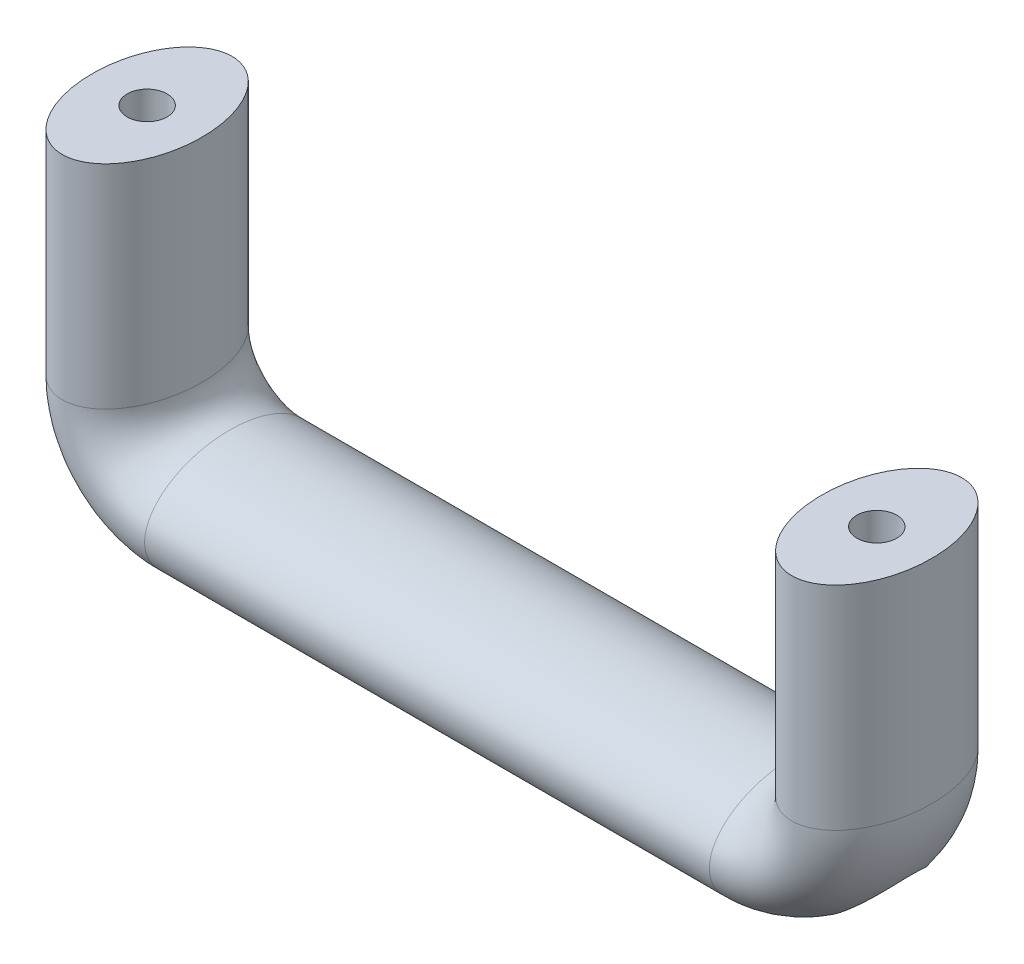
SolidWorks part; units mm, degrees
material "6061-T6 (SS)"
ref_plane "Front Plane" through (0, 0, 0) normal (0, 0, 1) x (1, 0, 0)
ref_plane "Top Plane" through (0, 0, 0) normal (0, 1, 0) x (1, 0, 0)
ref_plane "Right Plane" through (0, 0, 0) normal (1, 0, 0) x (0, 0, -1)
sketch "Sketch1" plane through (0, 0, 0) normal (0, 0, 1) x (1, 0, 0)
  line L0 (-57.9438, 46.8312) -> (-57.9438, 13.0969) construction
  line L1 (-44.8469, 0) -> (44.8469, 0) construction
  line L2 (57.9438, 13.0969) -> (57.9437, 46.8312) construction
  line L3 (-66.675, 46.8313) -> (-49.2125, 46.8313) construction
  line L4 (49.2125, 46.8312) -> (66.675, 46.8312) construction
  line L5 (-57.9438, -8.7312) -> (57.9438, -8.7312) construction
  line L7 (-61.1187, 46.8312) -> (-54.7688, 46.8312) construction
  line L8 (-61.1187, 46.8312) -> (-61.1187, 29.3687) construction
  line L9 (-61.1187, 29.3687) -> (-54.7687, 29.3687) construction
  line L10 (-54.7688, 46.8312) -> (-54.7687, 29.3687) construction
  line L11 (54.7688, 46.8312) -> (61.1187, 46.8312) construction
  line L12 (54.7688, 46.8312) -> (54.7688, 29.3687) construction
  line L13 (54.7688, 29.3687) -> (61.1187, 29.3687) construction
  line L14 (61.1187, 46.8312) -> (61.1187, 29.3687) construction
  arc A0 (-57.9438, 13.0969) -> (-44.8469, 0) centre (-44.8469, 13.0969) ccw construction
  arc A1 (44.8469, 0) -> (57.9438, 13.0969) centre (44.8469, 13.0969) ccw construction
  point P11 (-57.9438, 29.3687)
  dimension "D2" = 13.0969
  dimension "D1" = 8.7312
  dimension "A" = 115.8875
  dimension "Projected Dis" = 55.5625
  dimension "Thread Dia" = 6.35
  dimension "Thread Depth" = 17.4625
  dimension "width" = 17.4625
ref_plane "Plane1" through (0, 46.8312, 0) normal (0, 1, 0) x (-1, 0, 0)
sketch "Sketch2" plane through (0, 46.8312, 0) normal (0, 1, 0) x (-1, 0, 0)
  ellipse E0 centre (57.9438, 0) end of major axis (57.9438, -13.4937) minor radius 8.7312
  dimension "D1" = 26.9875
sketch "Sketch3" plane through (0, 0, 0) normal (0, 0, 1) x (1, 0, 0)
  line L0 (57.9438, 13.0969) -> (57.9437, 46.8312) construction
  line L1 (-44.8469, 0) -> (44.8469, 0) construction
  line L2 (-57.9438, 46.8312) -> (-57.9438, 13.0969) construction
  line L3 (57.9438, 13.0969) -> (57.9437, 46.8312)
  line L4 (-44.8469, 0) -> (44.8469, 0)
  line L5 (-57.9438, 46.8312) -> (-57.9438, 13.0969)
  arc A0 (44.8469, 0) -> (57.9438, 13.0969) centre (44.8469, 13.0969) ccw construction
  arc A1 (-57.9438, 13.0969) -> (-44.8469, 0) centre (-44.8469, 13.0969) ccw construction
  arc A2 (44.8469, 0) -> (57.9438, 13.0969) centre (44.8469, 13.0969) ccw
  arc A3 (-57.9438, 13.0969) -> (-44.8469, 0) centre (-44.8469, 13.0969) ccw
sketch "Sketch8" plane through (0, 46.8312, 0) normal (0, 1, 0) x (-1, 0, 0)
  line L0 (57.9438, -13.4937) -> (57.9438, 13.4937) construction
  dimension "height" = 26.9875
ref_plane "Plane2" through (-57.9438, 0, 0) normal (1, 0, 0) x (0, 0, -1)
sweep "Sweep1" add profiles "Sketch2" path "Sketch3"
sketch "Sketch4" plane through (0, 46.8312, 0) normal (0, 1, 0) x (-1, 0, 0)
  circle A0 centre (57.9438, 0) radius 3.175
extrude "Extrude1" cut sketch "Sketch4" against normal up to vertex (17.4625 mm away) up to point (-57.9438, 29.3687, 0)
sketch "Sketch9" plane through (0, 29.3687, 0) normal (0, 1, 0) x (1, 0, 0)
  circle A0 centre (-57.9438, 0) radius 5.08
  dimension "D1" = 10.16
extrude "Extrude2" cut sketch "Sketch9" along normal blind 5.5499 and the other way through all draft 1
mirror "Mirror1" about plane through (0, 0, 0) normal (1, 0, 0) of "Extrude2", "Extrude1"
equation "\"D1@Sketch1\" = \"width@Sketch1\"/2"
equation "\"D2@Sketch1\" = \"width@Sketch1\"*.750"
equation "\"D1@Sketch2\" = \"height@Sketch8\""
equation "\"D1@Sketch9\" = \"Thread Dia@Sketch1\"*1.6"
